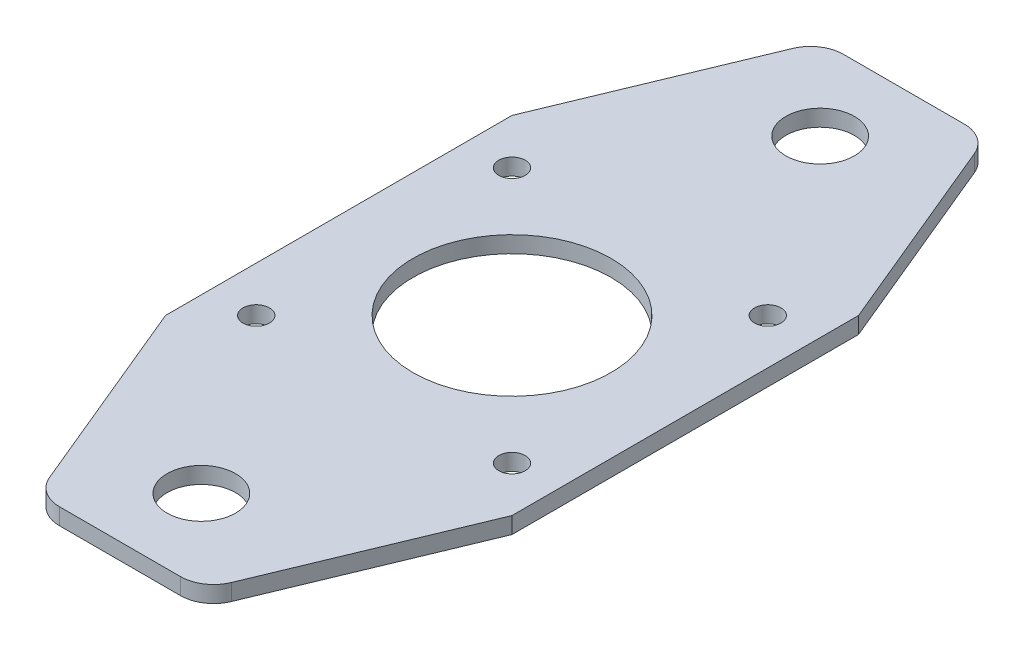
SolidWorks part; units mm, degrees
ref_plane "Front Plane" through (0, 0, 0) normal (0, 0, 1) x (1, 0, 0)
ref_plane "Top Plane" through (0, 0, 0) normal (0, 1, 0) x (1, 0, 0)
ref_plane "Right Plane" through (0, 0, 0) normal (1, 0, 0) x (0, 0, -1)
sketch "Sketch1" plane through (0, 0, 0) normal (0, 1, 0) x (1, 0, 0)
  line L0 (0, 54.328) -> (0, -44.5641) construction
  line L1 (-25.1307, 0) -> (26.2682, 0) construction
  line L2 (-7.3295, 47.5) -> (7.3295, 47.5)
  line L3 (-21, -21) -> (21, -21)
  line L4 (-21, -21) -> (-21, 21)
  line L5 (-21, 21) -> (21, 21)
  line L6 (21, -21) -> (21, 21)
  line L7 (-21, -21) -> (21, 21) construction
  line L8 (-21, 21) -> (21, -21) construction
  line L9 (11.0238, 45.0335) -> (21, 21)
  line L10 (-11.0238, 45.0335) -> (-21, 21)
  line L11 (-11.0238, -45.0335) -> (-21, -21)
  line L12 (11.0238, -45.0335) -> (21, -21)
  line L13 (-7.3295, -47.5) -> (7.3295, -47.5)
  circle A0 centre (0, 0) radius 12
  circle A1 centre (-15.5, 15.5) radius 1.6
  circle A2 centre (15.5, 15.5) radius 1.6
  circle A3 centre (15.5, -15.5) radius 1.6
  circle A4 centre (-15.5, -15.5) radius 1.6
  circle A5 centre (-0.1547, 37.5) radius 4.15
  arc A6 (11.0238, 45.0335) -> (7.3295, 47.5) centre (7.3295, 43.5) ccw
  arc A7 (-11.0238, -45.0335) -> (-7.3295, -47.5) centre (-7.3295, -43.5) ccw
  arc A8 (-11.0238, 45.0335) -> (-7.3295, 47.5) centre (-7.3295, 43.5) cw
  arc A9 (11.0238, -45.0335) -> (7.3295, -47.5) centre (7.3295, -43.5) cw
  circle A10 centre (-0.1547, -37.5) radius 4.15
  point P27 (10, 47.5)
  point P31 (0, 47.5)
  point P37 (0, -47.5)
  point P38 (10, -47.5)
  dimension "D1" = 24
  dimension "D2" = 3.2
  dimension "D3" = 10
  dimension "D4" = 15.5
  dimension "D7" = 8.3
  dimension "D8" = 16.5
  dimension "D9" = 10
  dimension "D10" = 4
  dimension "D5" = 42
  dimension "D6" = 42
extrude "Boss-Extrude1" add sketch "Sketch1" along normal blind 2 contours A9 L12 L3 L11 A7 L13 A10 | L3 L6 L5 L4 A2 A1 A0 A3 A4 | A8 L10 L5 L9 A6 L2 A5
